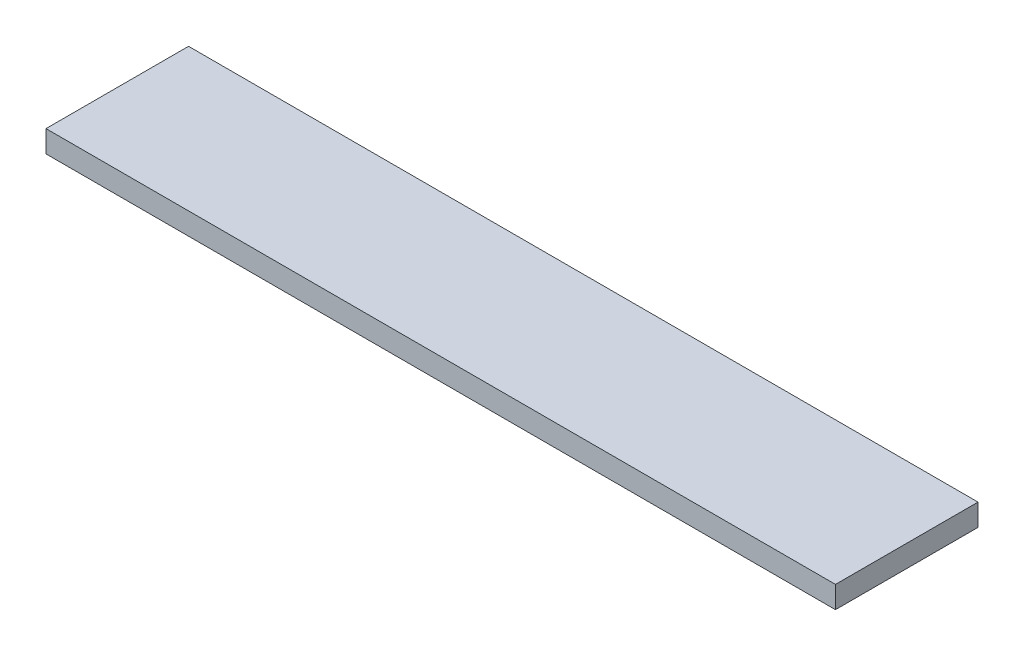
SolidWorks part; units mm, degrees
ref_plane "Plan de face" through (0, 0, 0) normal (0, 0, 1) x (1, 0, 0)
ref_plane "Plan de dessus" through (0, 0, 0) normal (0, 1, 0) x (1, 0, 0)
ref_plane "Plan de droite" through (0, 0, 0) normal (1, 0, 0) x (0, 0, -1)
sketch "Esquisse1" plane through (0, 0, 0) normal (0, 1, 0) x (1, 0, 0)
  line L1 (-228.6, 41.275) -> (228.6, 41.275)
  line L2 (-228.6, 41.275) -> (-228.6, -41.275)
  line L3 (-228.6, -41.275) -> (228.6, -41.275)
  line L4 (228.6, 41.275) -> (228.6, -41.275)
  line L5 (-228.6, 41.275) -> (228.6, -41.275) construction
  line L6 (-228.6, -41.275) -> (228.6, 41.275) construction
  point P0 (0, 0)
  dimension "D1" = 457.2
  dimension "D2" = 82.55
extrude "Boss.-Extru.1" add sketch "Esquisse1" along normal blind 12.7
